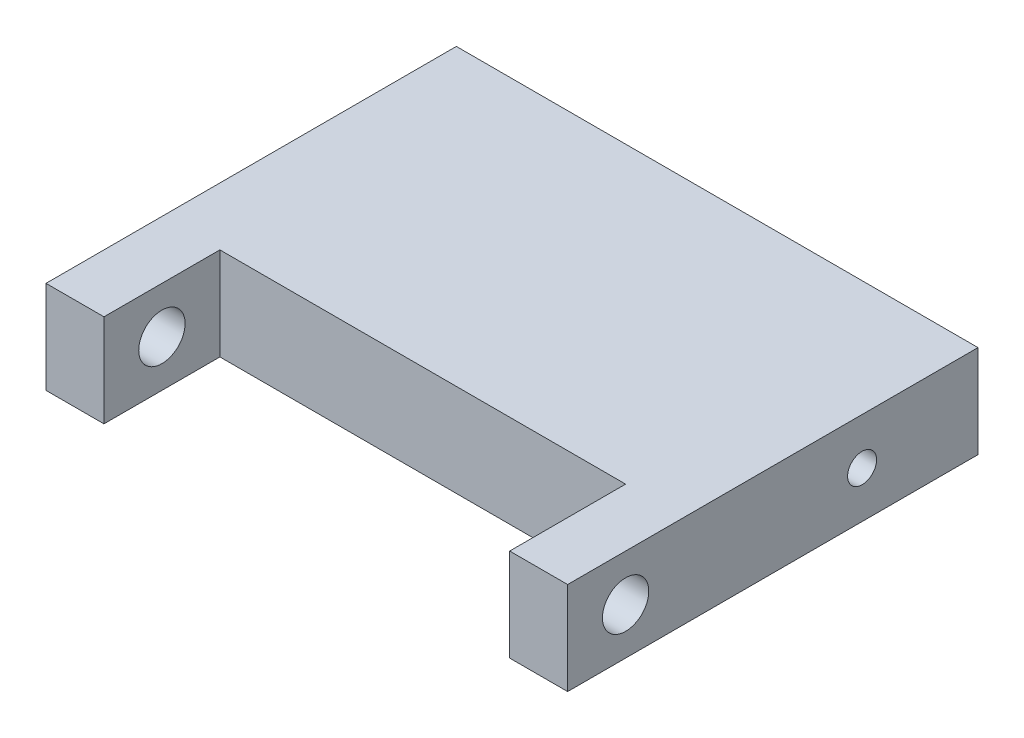
SolidWorks part; units mm, degrees
ref_plane "Front" through (0, 0, 0) normal (0, 0, 1) x (1, 0, 0)
ref_plane "Top" through (0, 0, 0) normal (0, 1, 0) x (1, 0, 0)
ref_plane "Right" through (0, 0, 0) normal (1, 0, 0) x (0, 0, -1)
sketch "Sketch1" plane through (0, 0, 0) normal (0, 1, 0) x (1, 0, 0)
  line L1 (0, 0) -> (45, 0)
  line L2 (0, 0) -> (0, 25.4)
  line L3 (0, 25.4) -> (45, 25.4)
  line L4 (45, 0) -> (45, 25.4)
  dimension "D1" = 45
  dimension "D2" = 25.4
extrude "Boss-Extrude1" add sketch "Sketch1" along normal blind 8
sketch "Sketch2" plane through (0, 0, 0) normal (0, 0, 1) x (1, 0, 0)
  line L0 (0, 8) -> (45, 8) construction
  line L1 (45, 0) -> (40, 0)
  line L2 (45, 0) -> (45, 8)
  line L3 (45, 8) -> (40, 8)
  line L4 (40, 0) -> (40, 8)
  dimension "D1" = 5
extrude "Boss-Extrude2" add sketch "Sketch2" along normal blind 10
sketch "Sketch3" plane through (40, 0, 0) normal (-1, 0, 0) x (0, 0, 1)
  line L0 (10, 4) -> (0, 4)
  line L1 (10, 8) -> (10, 0) construction
  line L2 (0, 8) -> (0, 0) construction
  circle A0 centre (5, 4) radius 2
  dimension "D1" = 5
extrude "Cut-Extrude1" cut sketch "Sketch3" against normal blind 30 contours A0
pattern_linear "LPattern1" count 2 spacing 40 along (-1, 0, 0) of "Boss-Extrude2", "Cut-Extrude1"
sketch "Sketch4" plane through (0, 0, 0) normal (-1, 0, 0) x (0, 0, 1)
  line L0 (-25.4, 4) -> (-15.4, 4)
  line L1 (-25.4, 8) -> (-25.4, 0) construction
  circle A0 centre (-15.4, 4) radius 1.25
  dimension "D1" = 10
extrude "Cut-Extrude2" cut sketch "Sketch4" against normal blind 8 contours A0
pattern_linear "LPattern2" count 2 spacing 37 along (1, 0, 0) of "Cut-Extrude2"
sketch "Sketch5" plane through (0, 0, -25.4) normal (0, 0, -1) x (-1, 0, 0)
  line L0 (245.7182, 0.1882) -> (-287.1874, 0.1882)
  line L1 (245.7182, 0.1882) -> (245.7182, 9.2784)
  line L2 (-287.1874, 0.1882) -> (-287.1874, 9.2784)
  line L3 (245.7182, 9.2784) -> (-287.1874, 9.2784)
  line L4 (245.7182, 0.1882) -> (-287.1874, 9.2784) construction
  line L5 (-287.1874, 0.1882) -> (245.7182, 9.2784) construction
  point P1 (-20.7346, 4.7333)
extrude "Boss-Extrude3" [suppressed] add sketch "Sketch5" along normal blind 1000
